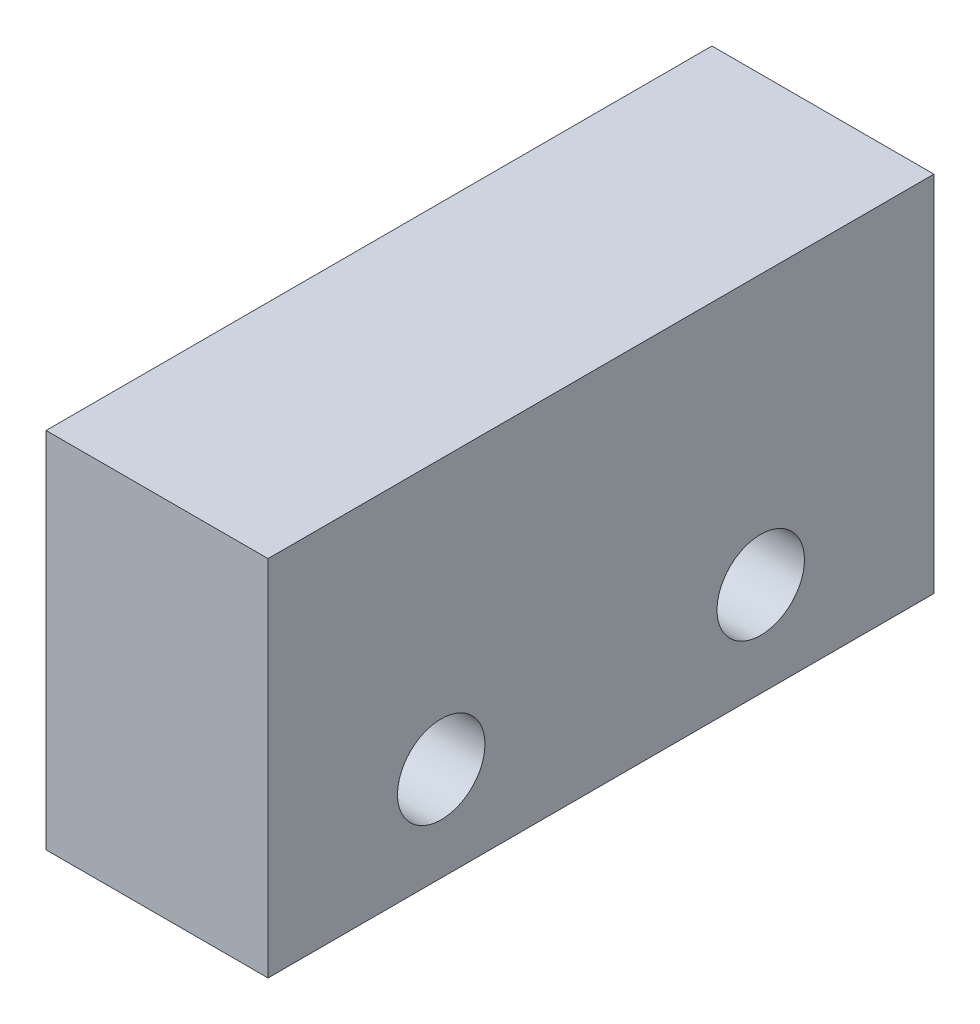
SolidWorks part; units mm, degrees
ref_plane "前视基准面" through (0, 0, 0) normal (0, 0, 1) x (1, 0, 0)
ref_plane "上视基准面" through (0, 0, 0) normal (0, 1, 0) x (1, 0, 0)
ref_plane "右视基准面" through (0, 0, 0) normal (1, 0, 0) x (0, 0, -1)
sketch "草图1" plane through (0, 0, 0) normal (1, 0, 0) x (0, 0, -1)
  line L1 (0, 0) -> (19.8, 0)
  line L2 (0, 0) -> (0, -10.8)
  line L3 (0, -10.8) -> (19.8, -10.8)
  line L4 (19.8, 0) -> (19.8, -10.8)
  dimension "D1" = 10.8
  dimension "D2" = 19.8
extrude "凸台-拉伸1" add sketch "草图1" along normal blind 6.6
sketch "草图2" plane through (6.6, 0, 0) normal (1, 0, 0) x (0, 0, -1)
  line L0 (5.15, -8) -> (14.65, -8) construction
  line L1 (0, -10.8) -> (19.8, -10.8) construction
  line L2 (5.15, -10.8) -> (5.15, -8) construction
  circle A0 centre (5.15, -8) radius 1.3
  circle A1 centre (14.65, -8) radius 1.3
  dimension "D1" = 9.5
  dimension "D2" = 2.8
extrude "切除-拉伸1" cut sketch "草图2" against normal blind 6.6
